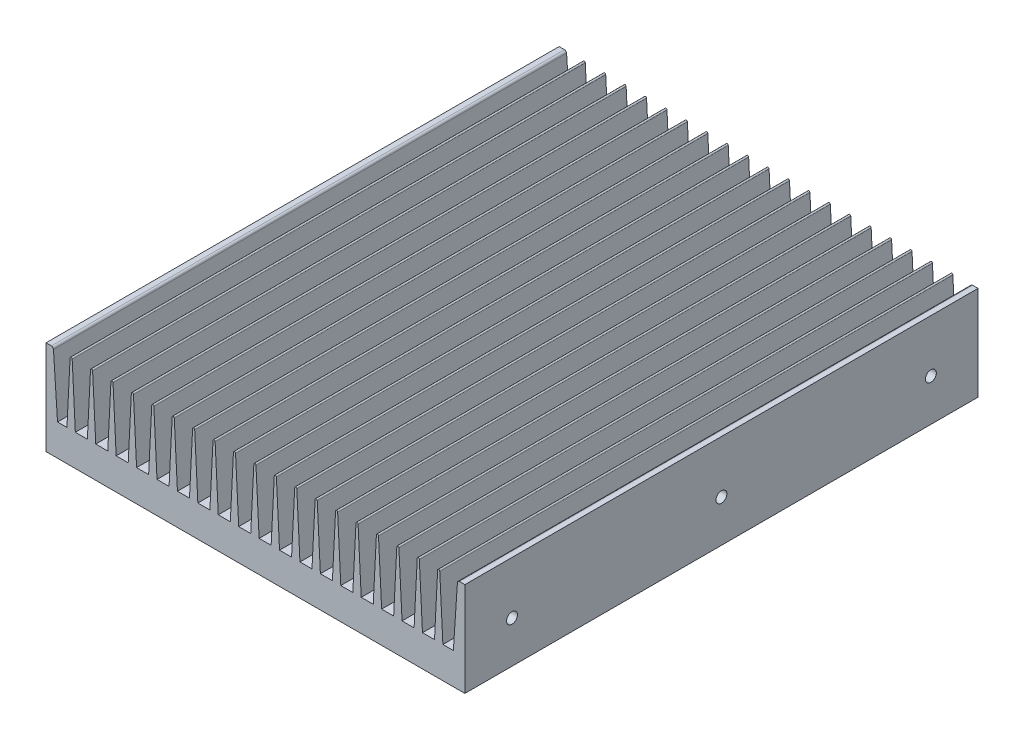
SolidWorks part; units mm, degrees
ref_plane "Спереди" through (0, 0, 0) normal (0, 0, 1) x (1, 0, 0)
ref_plane "Сверху" through (0, 0, 0) normal (0, 1, 0) x (1, 0, 0)
ref_plane "Справа" through (0, 0, 0) normal (1, 0, 0) x (0, 0, -1)
sketch "Эскиз1" plane through (0, 0, 0) normal (0, 0, 1) x (1, 0, 0)
  line L0 (0, 45) -> (2.5644, 45)
  line L1 (0, 0) -> (200, 0)
  line L2 (3.5622, 44.0665) -> (5.5, 15)
  line L3 (0, 45) -> (0, 0)
  line L4 (200, 45) -> (200, 0)
  line L5 (100, 63.7127) -> (100, -22.2582) construction
  line L8 (200, 45) -> (197.4356, 45)
  line L9 (196.4378, 44.0665) -> (194.5, 15)
  line L10 (5.5, 15) -> (194.5, 15)
  arc A0 (2.5644, 45) -> (3.5622, 44.0665) centre (2.5644, 44) cw
  arc A2 (197.4356, 45) -> (196.4378, 44.0665) centre (197.4356, 44) ccw
  point P18 (196.5, 45)
  dimension "D9" = 1
  dimension "D1" = 200
  dimension "D2" = 15
  dimension "D3" = 45
  dimension "D4" = 5.5
  dimension "D7" = 3.5
extrude "Вытянуть1" add sketch "Эскиз1" along normal blind 245
sketch "Эскиз2" plane through (0, 0, 245) normal (0, 0, 1) x (1, 0, 0)
  line L0 (194.5, 15) -> (5.5, 15) construction
  line L1 (11.5, 44.5) -> (10, 15)
  line L2 (12, 44.5) -> (12, 22.5548) construction
  line L3 (12.5, 44.5) -> (14, 15)
  line L4 (10, 15) -> (14, 15)
  line L6 (0, 45) -> (0, 0) construction
  arc A0 (11.5, 44.5) -> (12.5, 44.5) centre (12, 44.5) cw
  dimension "D1" = 30
  dimension "D3" = 0.5
  dimension "D2" = 4
  dimension "D4" = 12
  dimension "D5" = 1
extrude "Вытянуть3" add sketch "Эскиз2" against normal blind 245
pattern_curve "Кривая1" of "Вытянуть3" along edge at (100, 0, 0) parameters "D1"=19, "D3"=9.75, "D2"=1, "D4"=50
sketch "Эскиз7" plane through (0, 0, 0) normal (-1, 0, 0) x (0, 0, 1)
  line L0 (-24.1676, 20) -> (275.3481, 20) construction
  line L1 (122.5, 109.9776) -> (122.5, -31.6981) construction
  line L2 (245, 45) -> (245, 0) construction
  line L3 (0, 45) -> (0, 0) construction
  line L4 (245, 0) -> (0, 0) construction
  circle A0 centre (22.5, 20) radius 2.6
  circle A1 centre (222.5, 20) radius 2.6
  circle A2 centre (122.5, 20) radius 2.6
  dimension "D2" = 5.2
  dimension "D3" = 200
  dimension "D1" = 20
extrude "Вырез-Вытянуть4" cut sketch "Эскиз7" against normal blind 6
sketch "Эскиз8" plane through (200, 0, 0) normal (1, 0, 0) x (0, 0, -1)
  line L0 (9.57, 30) -> (-255.3048, 30) construction
  line L1 (-245, 45) -> (0, 45) construction
  line L2 (-122.5, 20) -> (-122.5, -38.851) construction
  line L3 (0, 0) -> (0, 45) construction
  line L4 (-245, 0) -> (-245, 45) construction
  circle A0 centre (-80, 30) radius 4.5
  circle A1 centre (-165, 30) radius 3.4
  dimension "D2" = 9
  dimension "D3" = 6.8
  dimension "D5" = 80
  dimension "D1" = 15
  dimension "D4" = 80
extrude "Вырез-Вытянуть5" cut sketch "Эскиз8" against normal blind 6
sketch "Эскиз9" plane through (200, 0, 0) normal (1, 0, 0) x (0, 0, -1)
  circle A0 centre (-22.5, 20) radius 2.6 construction
  circle A1 centre (-22.5, 20) radius 2.6
  circle A2 centre (-122.5, 20) radius 2.6 construction
  circle A3 centre (-122.5, 20) radius 2.6
  circle A4 centre (-222.5, 20) radius 2.6 construction
  circle A5 centre (-222.5, 20) radius 2.6
extrude "Вырез-Вытянуть6" cut sketch "Эскиз9" against normal blind 6
cosmetic thread "Условное изображение резьбы9" parameters "D1"=4.34, "D2"=6
cosmetic thread "Условное изображение резьбы10" parameters "D1"=4.34, "D2"=6
cosmetic thread "Условное изображение резьбы11" parameters "D1"=4.34, "D2"=6
cosmetic thread "Условное изображение резьбы35" parameters "D2"=6
cosmetic thread "Условное изображение резьбы36" parameters "D2"=6
cosmetic thread "Условное изображение резьбы37" parameters "D2"=6
sketch "Эскиз11" plane through (0, 0, 0) normal (-1, 0, 0) x (0, 0, 1)
  circle A0 centre (22.5, 20) radius 2.6 construction
  circle A1 centre (22.5, 20) radius 2.6
  circle A2 centre (122.5, 20) radius 2.6 construction
  circle A3 centre (122.5, 20) radius 2.6
  circle A4 centre (222.5, 20) radius 2.6 construction
  circle A5 centre (222.5, 20) radius 2.6
extrude "Вытянуть4" add sketch "Эскиз11" against normal up to surface (5.34 mm away)
sketch "Эскиз12" plane through (200, 0, 0) normal (1, 0, 0) x (0, 0, -1)
  circle A0 centre (-80, 30) radius 4.5 construction
  circle A1 centre (-80, 30) radius 4.5
  circle A2 centre (-165, 30) radius 3.4 construction
  circle A3 centre (-165, 30) radius 3.4
extrude "Вытянуть5" add sketch "Эскиз12" against normal up to surface (4.5 mm away)
sketch "Эскиз19" plane through (0, 0, 0) normal (-1, 0, 0) x (0, 0, 1)
  circle A0 centre (222.5, 20) radius 2.6 construction
  circle A1 centre (222.5, 20) radius 2.6
  circle A2 centre (122.5, 20) radius 2.6 construction
  circle A3 centre (122.5, 20) radius 2.6
  circle A4 centre (22.5, 20) radius 2.6 construction
  circle A5 centre (22.5, 20) radius 2.6
extrude "Вырез-Вытянуть12" cut sketch "Эскиз19" against normal blind 8
cosmetic thread "Условное изображение резьбы32" parameters "D2"=6
cosmetic thread "Условное изображение резьбы33" parameters "D2"=6
cosmetic thread "Условное изображение резьбы34" parameters "D2"=6
sketch "Эскиз21" plane through (0, 0, 0) normal (0, -1, 0) x (1, 0, 0)
  line L0 (0, 0) -> (200, 0) construction
  line L1 (189, 205) -> (304.2911, 205) construction
  line L2 (10, 145) -> (10, 10) construction
  line L3 (10, 145) -> (130, 145) construction
  line L4 (130, 145) -> (130, 10) construction
  line L5 (130, 10) -> (10, 10) construction
  line L6 (50.25, 141.4) -> (83.3996, 141.4) construction
  line L7 (50.25, 141.4) -> (50.25, 161.6649) construction
  line L8 (90.25, 141.4) -> (90.25, 2.5412) construction
  line L9 (50.25, 57.6) -> (72.3234, 57.6) construction
  line L10 (10, 10) -> (130, 10) construction
  line L12 (0, 245) -> (0, 0) construction
  line L13 (10, 186) -> (10, 234) construction
  line L15 (0, 245) -> (200, 245) construction
  line L16 (200, 245) -> (200, 0) construction
  line L21 (18.7035, 234) -> (81.3799, 234) construction
  line L22 (18.7035, 186) -> (77.3385, 186) construction
  circle A0 centre (36.5, 47) radius 2.6
  circle A1 centre (10, 145) radius 1.6
  circle A2 centre (10, 10) radius 1.6
  circle A3 centre (130, 10) radius 1.6
  circle A4 centre (130, 145) radius 1.6
  circle A5 centre (50.25, 141.4) radius 1.6
  circle A6 centre (90.25, 141.4) radius 1.6
  circle A7 centre (50.25, 57.6) radius 1.6
  circle A8 centre (90.25, 57.6) radius 1.6
  circle A9 centre (93, 18.5) radius 1.3
  circle A10 centre (134, 205) radius 2.1
  circle A11 centre (155, 145) radius 2.1
  circle A12 centre (189, 205) radius 2.1
  circle A13 centre (155, 10) radius 2.1
  circle A21 centre (76, 234) radius 1.6
  circle A22 centre (10, 234) radius 1.6
  circle A23 centre (10, 186) radius 1.6
  circle A24 centre (76, 186) radius 1.6
  dimension "D8" = 10
  dimension "D11" = 40.25
  dimension "D12" = 3.6
  dimension "D10" = 4.2
  dimension "D13" = 26.5
  dimension "D15" = 37
  dimension "D17" = 5.2
  dimension "D18" = 11
  dimension "D23" = 2.6
  dimension "D24" = 10
  dimension "D25" = 25
  dimension "D26" = 4.2
  dimension "D27" = 66
  dimension "D20" = 25
  dimension "D28" = 3.2
  dimension "D9" = 37
  dimension "D14" = 135
  dimension "D16" = 8.5
  dimension "D19" = 40
  dimension "D3" = 10
  dimension "D29" = 48
  dimension "D21" = 4.2
  dimension "D22" = 40
  dimension "D30" = 66
  dimension "D33" = 3.2
  dimension "D34" = 55
  dimension "D35" = 3.2
  dimension "D4" = 120
  dimension "D5" = 135
  dimension "D6" = 40
  dimension "D7" = 83.8
  dimension "D31" = 11
  dimension "D32" = 10
extrude "Вырез-Вытянуть13" cut sketch "Эскиз21" against normal blind 10
cosmetic thread "Условное изображение резьбы38" parameters "D1"=10, "D2"=4
cosmetic thread "Условное изображение резьбы39" parameters "D1"=10, "D2"=4
cosmetic thread "Условное изображение резьбы40" parameters "D1"=10, "D2"=4
cosmetic thread "Условное изображение резьбы41" parameters "D1"=10, "D2"=4
cosmetic thread "Условное изображение резьбы42" parameters "D1"=8, "D2"=3
cosmetic thread "Условное изображение резьбы43" parameters "D1"=8, "D2"=4
cosmetic thread "Условное изображение резьбы44" parameters "D1"=8, "D2"=4
cosmetic thread "Условное изображение резьбы45" parameters "D1"=8, "D2"=4
cosmetic thread "Условное изображение резьбы46" parameters "D1"=8, "D2"=4
cosmetic thread "Условное изображение резьбы47" parameters "D1"=8, "D2"=5
cosmetic thread "Условное изображение резьбы48" parameters "D2"=5
cosmetic thread "Условное изображение резьбы49" parameters "D2"=5
cosmetic thread "Условное изображение резьбы55" parameters "D1"=8, "D2"=4
cosmetic thread "Условное изображение резьбы56" parameters "D1"=8, "D2"=4
cosmetic thread "Условное изображение резьбы57" parameters "D1"=8, "D2"=4
cosmetic thread "Условное изображение резьбы58" parameters "D1"=8, "D2"=4
cosmetic thread "Условное изображение резьбы59" parameters "D2"=5
